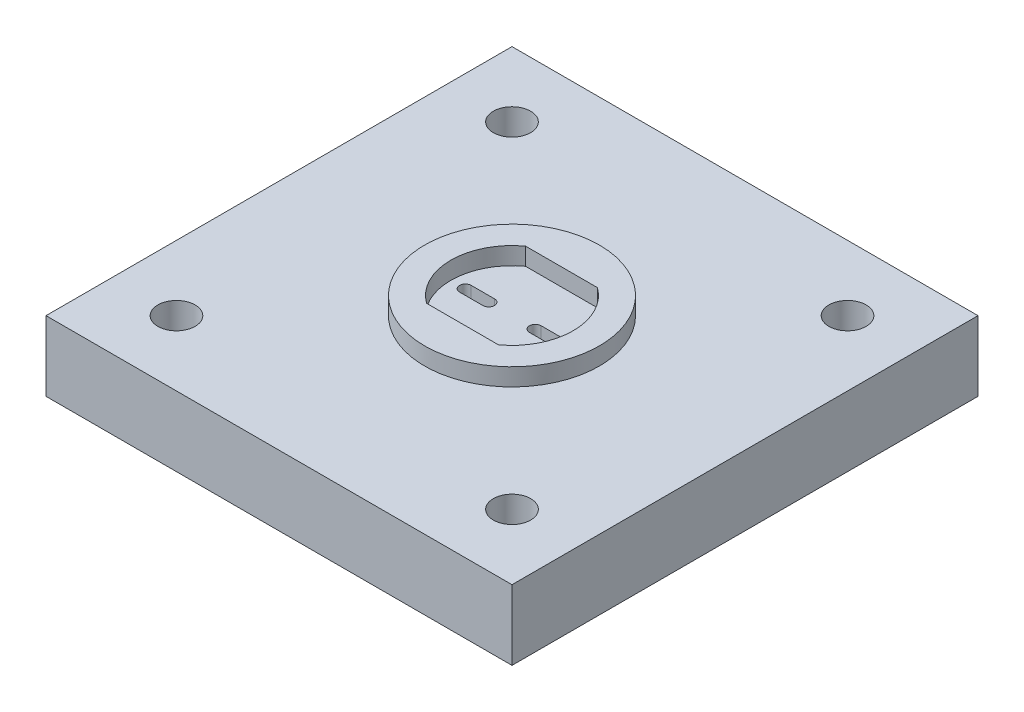
SolidWorks part; units mm, degrees
ref_plane "前视基准面" through (0, 0, 0) normal (0, 0, 1) x (1, 0, 0)
ref_plane "上视基准面" through (0, 0, 0) normal (0, 1, 0) x (1, 0, 0)
ref_plane "右视基准面" through (0, 0, 0) normal (1, 0, 0) x (0, 0, -1)
other "Configuration Table"
sketch "Sketch1" plane through (0, 0, 0) normal (0, 1, 0) x (1, 0, 0)
  line L0 (20, 40) -> (20, 0) construction
  line L1 (0, 0) -> (40, 0)
  line L2 (0, 0) -> (0, 40)
  line L3 (0, 40) -> (40, 40)
  line L4 (40, 0) -> (40, 40)
  circle A0 centre (5.6, 34.4) radius 1.6
  circle A1 centre (5.6, 5.6) radius 1.6
  circle A2 centre (34.4, 34.4) radius 1.6
  circle A3 centre (34.4, 5.6) radius 1.6
  dimension "D3" = 28.8
  dimension "D4" = 3.2
  dimension "D5" = 3.2
  dimension "D6" = 5.6
  dimension "D7" = 5.6
  dimension "D8" = 5.6
  dimension "D9" = 3.2
  dimension "D10" = 28.8
  dimension "D11" = 5.6
  dimension "D12" = 3.2
  dimension "D13" = 5.6
  dimension "D14" = 5.6
  dimension "D1" = 40
  dimension "D2" = 40
extrude "Boss-Extrude1" add sketch "Sketch1" along normal blind 6
sketch "Sketch2" plane through (0, 6, 0) normal (0, 1, 0) x (1, 0, 0)
  line L0 (20, 40) -> (20, 0) construction
  line L1 (40, 40) -> (0, 40) construction
  line L2 (0, 0) -> (40, 0) construction
  line L3 (0, 20) -> (40, 20) construction
  line L4 (0, 40) -> (0, 0) construction
  line L5 (40, 0) -> (40, 40) construction
  line L6 (16.9178, 24.25) -> (23.0822, 24.25)
  line L7 (16.9178, 15.75) -> (23.0822, 15.75)
  circle A0 centre (20, 20) radius 5.25
  circle A1 centre (20, 20) radius 7.5
  dimension "D1" = 10.5
  dimension "D2" = 8.5
  dimension "D4" = 15
  dimension "D3" = 4.25
extrude "Boss-Extrude2" add sketch "Sketch2" along normal blind 1.5 contours A1 A0 | L6 A0 | L7 A0
sketch "Sketch4" plane through (0, 6, 0) normal (0, 1, 0) x (1, 0, 0)
  line L0 (16, 20) -> (18, 20) construction
  line L1 (16, 20.5) -> (18, 20.5)
  line L2 (16, 19.5) -> (18, 19.5)
  line L3 (24, 20) -> (22, 20) construction
  line L4 (24, 19.5) -> (22, 19.5)
  line L5 (24, 20.5) -> (22, 20.5)
  arc A0 (16, 20.5) -> (16, 19.5) centre (16, 20) ccw
  arc A1 (18, 19.5) -> (18, 20.5) centre (18, 20) ccw
  arc A2 (24, 19.5) -> (24, 20.5) centre (24, 20) ccw
  arc A3 (22, 20.5) -> (22, 19.5) centre (22, 20) ccw
  arc A4 (16.9178, 24.25) -> (16.9178, 15.75) centre (20, 20) ccw construction
  arc A5 (23.0822, 15.75) -> (23.0822, 24.25) centre (20, 20) ccw construction
  point P3 (17, 20)
  point P8 (23, 20)
  dimension "D1" = 0.5
  dimension "D2" = 0.5
  dimension "D3" = 2
  dimension "D4" = 4
  dimension "D5" = 4
  dimension "D6" = 2
extrude "Cut-Extrude1" cut sketch "Sketch4" against normal blind 21.5
